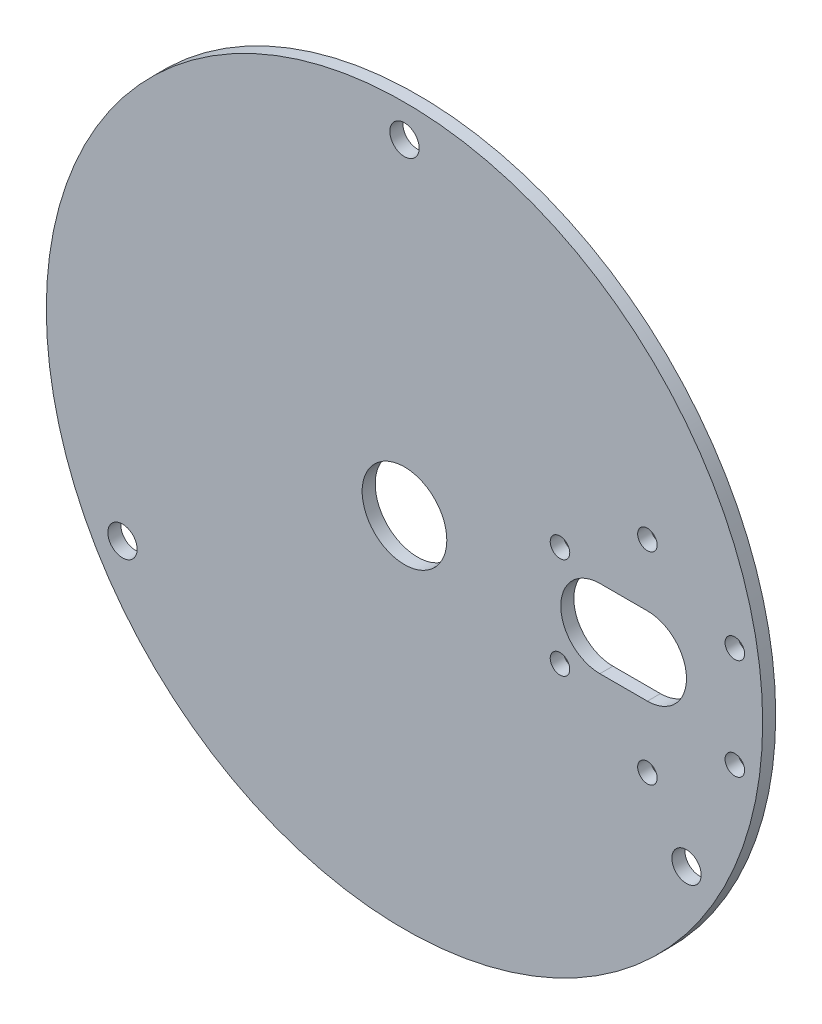
SolidWorks part; units mm, degrees
material "Thornel Mat VMA"
ref_plane "前视基准面" through (0, 0, 0) normal (0, 0, 1) x (1, 0, 0)
ref_plane "上视基准面" through (0, 0, 0) normal (0, 1, 0) x (1, 0, 0)
ref_plane "右视基准面" through (0, 0, 0) normal (1, 0, 0) x (0, 0, -1)
other "Configuration Table"
sketch "草图1" plane through (0, 0, 0) normal (0, 0, 1) x (1, 0, 0)
  line L0 (30, -999.9718) -> (30, 49000.0282) construction
  line L1 (37.3, 0) -> (30, 0) construction
  line L2 (37.3, -6) -> (30, -6)
  line L3 (37.3, 6) -> (30, 6)
  circle A0 centre (0, 0) radius 55
  circle A1 centre (37.3, 0) radius 15.5 construction
  circle A2 centre (37.3, 15.5) radius 1.5
  circle A3 centre (50.7234, 7.75) radius 1.5
  circle A4 centre (50.7234, -7.75) radius 1.5
  circle A5 centre (37.3, -15.5) radius 1.5
  circle A6 centre (23.8766, -7.75) radius 1.5
  circle A7 centre (23.8766, 7.75) radius 1.5
  arc A8 (37.3, -6) -> (37.3, 6) centre (37.3, 0) ccw
  arc A9 (30, 6) -> (30, -6) centre (30, 0) ccw
  circle A10 centre (0, 0) radius 6.5
  point P10 (33.65, 0)
  point P21 (37.3, 0)
  dimension "D1" = 31
  dimension "D2" = 110
  dimension "D5" = 3
  dimension "D7" = 6
  dimension "D8" = 13
  dimension "D3" = 7.3
  dimension "D4" = 30
  dimension "D6" = 6
extrude "凸台-拉伸1" add sketch "草图1" along normal blind 2
sketch "草图3" plane through (0, 0, 2) normal (0, 0, 1) x (1, 0, 0)
  circle A0 centre (0, 0) radius 50 construction
  circle A1 centre (0, 50) radius 2.25
  circle A2 centre (43.3013, -25) radius 2.25
  circle A3 centre (-43.3013, -25) radius 2.25
  point P12 (0, 0)
  dimension "D1" = 100
  dimension "D2" = 4.5
  dimension "D3" = 3
extrude "切除-拉伸1" cut sketch "草图3" against normal through all
